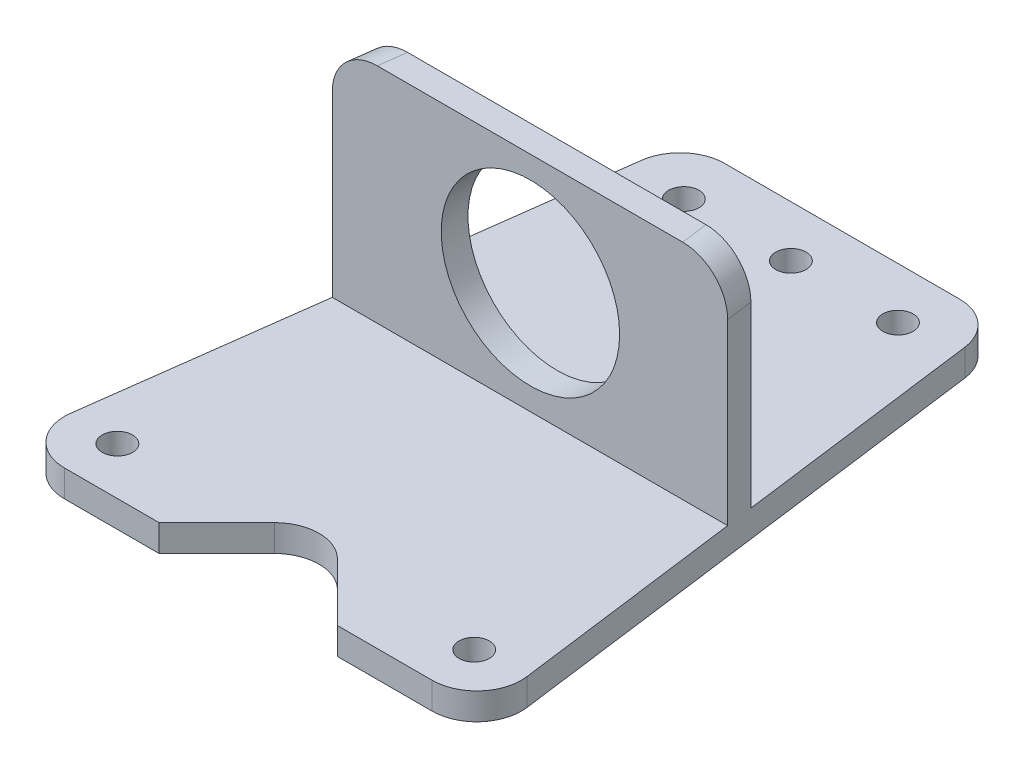
SolidWorks part; units mm, degrees
ref_plane "前视基准面" through (0, 0, 0) normal (0, 0, 1) x (1, 0, 0)
ref_plane "上视基准面" through (0, 0, 0) normal (0, 1, 0) x (1, 0, 0)
ref_plane "右视基准面" through (0, 0, 0) normal (1, 0, 0) x (0, 0, -1)
other "Configuration Table"
sketch "草图1" plane through (0, 0, 0) normal (0, 1, 0) x (1, 0, 0)
  line L0 (0, 364.5502) -> (0, -533.8776) construction
  line L1 (-17.5577, -482.8083) -> (17.5577, -482.8083)
  line L3 (-17.5577, -482.8083) -> (-26.3164, -549.3771)
  line L4 (17.5577, -482.8083) -> (26.3164, -549.3771)
  line L6 (-26.3164, -549.3771) -> (26.3164, -549.3771)
  line L10 (0, -542.9139) -> (0, -668.0813) construction
  circle A0 centre (-20, -544.0504) radius 1.7
  circle A1 centre (20, -544.0504) radius 1.7
  circle A2 centre (0, -488.5504) radius 1.7
  circle A3 centre (-12, -488.5504) radius 1.7
  circle A4 centre (12, -488.5504) radius 1.7
  point P8 (0, -482.8083)
  point P9 (0, -542.9139)
  point P27 (0, -544.0504)
  dimension "D2" = 40
  dimension "D3" = 24
  dimension "D4" = 55.5
extrude "凸台-拉伸2" add sketch "草图1" along normal blind 3
sketch "草图3" plane through (0, 3, 0) normal (0, 1, 0) x (1, 0, 0)
  line L0 (20, -544.0504) -> (-20, -544.0504) construction
  line L1 (0, -488.5504) -> (0, -544.0504) construction
  line L2 (-11.1968, -510.5728) -> (11.5513, -510.5728) construction
  line L8 (-18.3884, -520.4581) -> (21.0776, -511.5346) construction
  line L9 (-21.0776, -511.5346) -> (18.3884, -520.4581) construction
  line L10 (-17.5577, -482.8083) -> (-26.3164, -549.3771) construction
  line L14 (21.767, -514.8004) -> (-21.767, -514.8004)
  line L15 (22.1617, -517.8004) -> (-22.1617, -517.8004)
  line L16 (-21.767, -514.8004) -> (-22.1617, -517.8004)
  line L17 (21.767, -514.8004) -> (22.1617, -517.8004)
  point P9 (0, -516.3004)
  point P19 (0, -516.3004)
  point P25 (0, -516.3004)
  point P28 (0, -514.8004)
  point P31 (0, -517.8004)
extrude "凸台-拉伸3" add sketch "草图3" along normal blind 25
sketch "草图4" plane through (0, 0, 517.8004) normal (0, 0, 1) x (1, 0, 0)
  circle A0 centre (0.0514, 15.498) radius 10
extrude "切除-拉伸1" cut sketch "草图4" against normal blind 10 contours A0
sketch "草图5" plane through (0, 3, 0) normal (0, 1, 0) x (1, 0, 0)
  line L0 (0, -549.3771) -> (10, -549.3771)
  line L1 (-26.3164, -549.3771) -> (26.3164, -549.3771) construction
  line L2 (10, -549.3771) -> (0, -539.3771)
  line L3 (0, -539.3771) -> (-10, -549.3771)
  line L4 (-10, -549.3771) -> (0, -549.3771)
extrude "切除-拉伸2" cut sketch "草图5" against normal blind 10
fillet "圆角1" radius 5 7 edges at (-21.9644, 28, 516.3004) (21.9644, 28, 516.3004) (17.5577, 1.5, 482.8083) (-17.5577, 1.5, 482.8083) (26.3164, 1.5, 549.3771) (-26.3164, 1.5, 549.3771) (0, 1.5, 539.3771)
